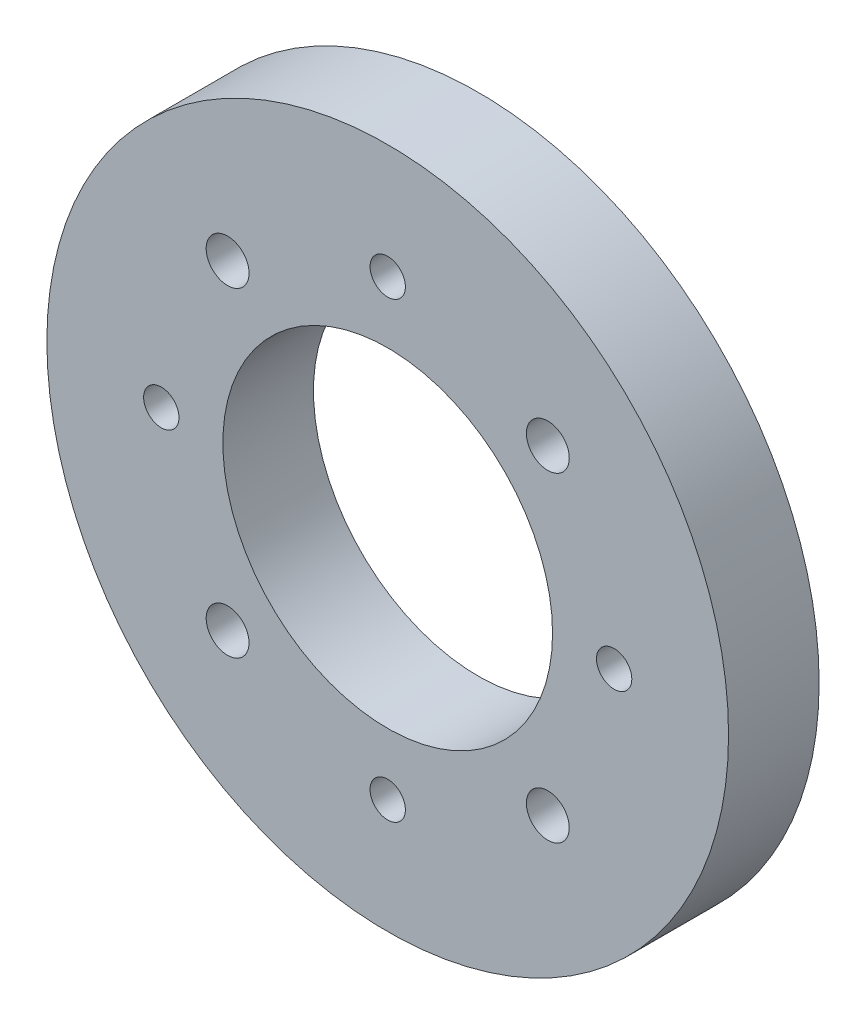
SolidWorks part; units mm, degrees
material "Balsa"
ref_plane "Front Plane" through (0, 0, 0) normal (0, 0, 1) x (1, 0, 0)
ref_plane "Top Plane" through (0, 0, 0) normal (0, 1, 0) x (1, 0, 0)
ref_plane "Right Plane" through (0, 0, 0) normal (1, 0, 0) x (0, 0, -1)
sketch "Sketch1" plane through (0, 0, 0) normal (0, 0, 1) x (1, 0, 0)
  circle A0 centre (0, 0) radius 22.5
  circle A1 centre (0, 0) radius 11
  circle A2 centre (0, 0) radius 15 construction
  circle A3 centre (0, 15) radius 1.25
  circle A4 centre (10.6066, 10.6066) radius 1.5
  circle A5 centre (15, 0) radius 1.25
  circle A6 centre (10.6066, -10.6066) radius 1.5
  circle A7 centre (0, -15) radius 1.25
  circle A8 centre (-10.6066, -10.6066) radius 1.5
  circle A9 centre (-15, 0) radius 1.25
  circle A10 centre (-10.6066, 10.6066) radius 1.5
  dimension "D1" = 45
  dimension "D2" = 22
  dimension "D3" = 30
  dimension "D4" = 2.5
  dimension "D5" = 3
  dimension "D6" = 45
extrude "Boss-Extrude1" add sketch "Sketch1" along normal blind 6
other "Move Face1" face at (11, 0, 6) face at (22.5, 0, 6) face at (1.25, 15, 6) face at (12.1066, 10.6066, 6) face at (16.25, 0, 6) face at (12.1066, -10.6066, 6) face at (1.25, -15, 6) face at (-9.1066, -10.6066, 6) face at (-13.75, 0, 6) face at (-9.1066, 10.6066, 6) parameters "D1"=0.08
